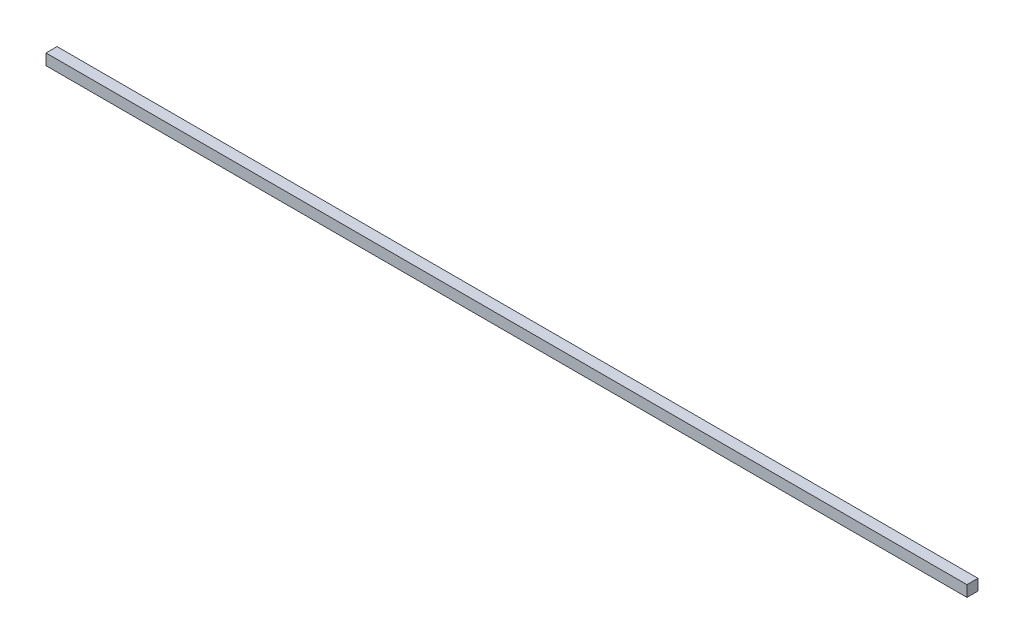
SolidWorks part; units mm, degrees
ref_plane "前视基准面" through (0, 0, 0) normal (0, 0, 1) x (1, 0, 0)
ref_plane "上视基准面" through (0, 0, 0) normal (0, 1, 0) x (1, 0, 0)
ref_plane "右视基准面" through (0, 0, 0) normal (1, 0, 0) x (0, 0, -1)
sketch "草图1" plane through (0, 0, 0) normal (1, 0, 0) x (0, 0, -1)
  line L1 (-15, 15) -> (15, 15)
  line L2 (-15, 15) -> (-15, -15)
  line L3 (-15, -15) -> (15, -15)
  line L4 (15, 15) -> (15, -15)
  line L5 (0, -15) -> (0, 15) construction
  line L6 (-15, 0) -> (15, 0) construction
  point P0 (0, 0)
  dimension "D1" = 30
extrude "凸台-拉伸1" add sketch "草图1" along normal blind 2502
